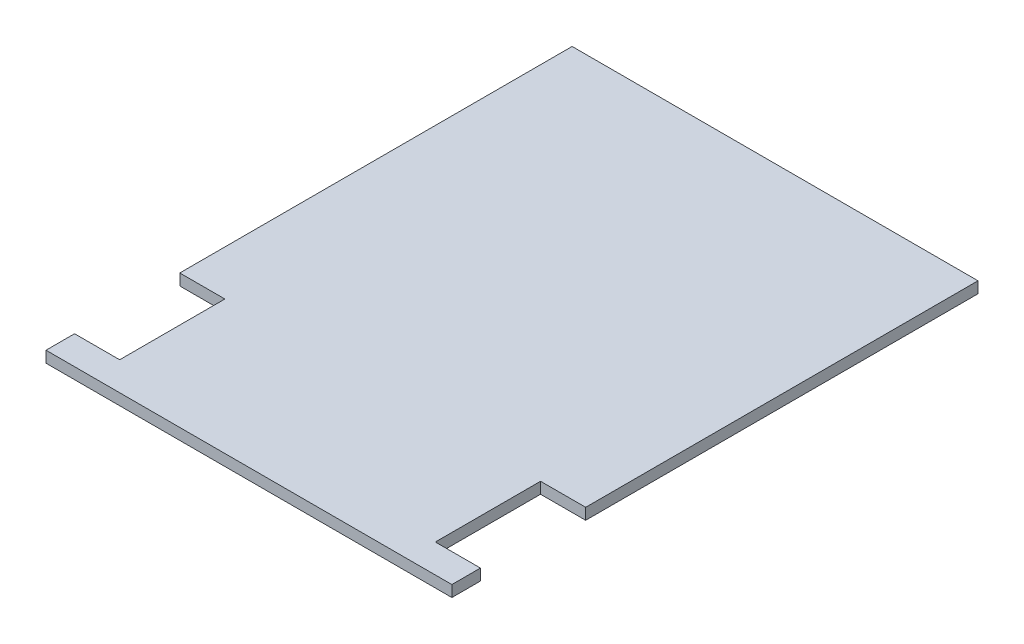
SolidWorks part; units mm, degrees
ref_plane "Front Plane" through (0, 0, 0) normal (0, 0, 1) x (1, 0, 0)
ref_plane "Top Plane" through (0, 0, 0) normal (0, 1, 0) x (1, 0, 0)
ref_plane "Right Plane" through (0, 0, 0) normal (1, 0, 0) x (0, 0, -1)
sketch "Sketch1" plane through (0, 0, 0) normal (0, 1, 0) x (1, 0, 0)
  line L0 (-19.3852, 35) -> (7.6148, 35)
  line L1 (-5.8852, 0) -> (-5.8852, 35) construction
  line L2 (7.6148, 35) -> (7.6148, 8.9)
  line L3 (7.6148, 8.9) -> (4.6148, 8.9)
  line L4 (4.6148, 8.9) -> (4.6148, 1.9)
  line L5 (4.6148, 1.9) -> (7.6148, 1.9)
  line L6 (7.6148, 1.9) -> (7.6148, 0)
  line L7 (7.6148, 0) -> (-19.3852, 0)
  line L8 (-19.3852, 1.9) -> (-19.3852, 0)
  line L9 (-16.3852, 1.9) -> (-19.3852, 1.9)
  line L10 (-16.3852, 8.9) -> (-16.3852, 1.9)
  line L11 (-19.3852, 8.9) -> (-16.3852, 8.9)
  line L12 (-19.3852, 35) -> (-19.3852, 8.9)
  point P4 (0, 0)
  point P8 (-5.8852, 35)
  dimension "D1" = 1.9
  dimension "D2" = 35
  dimension "D3" = 7
  dimension "D4" = 3
  dimension "D5" = 3
  dimension "D6" = 27
extrude "Boss-Extrude1" add sketch "Sketch1" along normal blind 0.75
